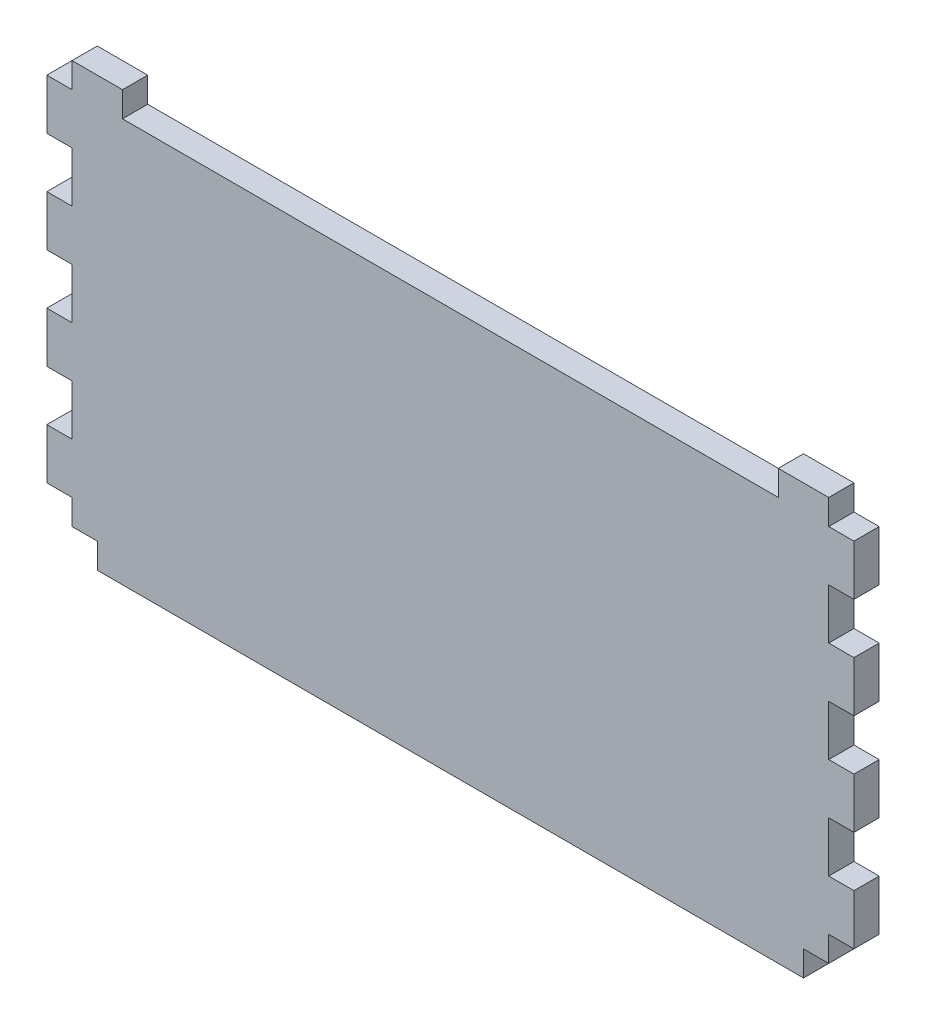
SolidWorks part; units mm, degrees
ref_plane "Plan de face" through (0, 0, 0) normal (0, 0, 1) x (1, 0, 0)
ref_plane "Plan de dessus" through (0, 0, 0) normal (0, 1, 0) x (1, 0, 0)
ref_plane "Plan de droite" through (0, 0, 0) normal (1, 0, 0) x (0, 0, -1)
sketch "Esquisse1" plane through (0, 0, 0) normal (0, 0, 1) x (1, 0, 0)
  line L32 (-83.2481, -165.0972) -> (-83.2481, -160.0972)
  line L33 (-83.2481, -85.0972) -> (66.7519, -85.0972)
  line L50 (-83.2481, -165.0972) -> (66.7519, -165.0972)
  line L52 (-83.2481, -90.0972) -> (-88.2481, -90.0972)
  line L54 (-83.2481, -100.0972) -> (-88.2481, -100.0972)
  line L55 (-88.2481, -90.0972) -> (-88.2481, -100.0972)
  line L56 (-83.2481, -110.0972) -> (-88.2481, -110.0972)
  line L58 (-83.2481, -120.0972) -> (-88.2481, -120.0972)
  line L59 (-88.2481, -110.0972) -> (-88.2481, -120.0972)
  line L60 (-83.2481, -130.0972) -> (-88.2481, -130.0972)
  line L62 (-83.2481, -140.0972) -> (-88.2481, -140.0972)
  line L63 (-88.2481, -130.0972) -> (-88.2481, -140.0972)
  line L64 (-83.2481, -150.0972) -> (-88.2481, -150.0972)
  line L66 (-83.2481, -160.0972) -> (-88.2481, -160.0972)
  line L67 (-88.2481, -150.0972) -> (-88.2481, -160.0972)
  line L68 (-83.2481, -150.0972) -> (-83.2481, -140.0972)
  line L69 (-83.2481, -130.0972) -> (-83.2481, -120.0972)
  line L70 (-83.2481, -110.0972) -> (-83.2481, -100.0972)
  line L71 (-83.2481, -90.0972) -> (-83.2481, -85.0972)
  line L72 (66.7519, -165.0972) -> (66.7519, -160.0972)
  line L73 (66.7519, -90.0972) -> (71.7519, -90.0972)
  line L75 (66.7519, -100.0972) -> (71.7519, -100.0972)
  line L76 (71.7519, -90.0972) -> (71.7519, -100.0972)
  line L77 (66.7519, -110.0972) -> (71.7519, -110.0972)
  line L79 (66.7519, -120.0972) -> (71.7519, -120.0972)
  line L80 (71.7519, -110.0972) -> (71.7519, -120.0972)
  line L81 (66.7519, -130.0972) -> (71.7519, -130.0972)
  line L83 (66.7519, -140.0972) -> (71.7519, -140.0972)
  line L84 (71.7519, -130.0972) -> (71.7519, -140.0972)
  line L85 (66.7519, -150.0972) -> (71.7519, -150.0972)
  line L87 (66.7519, -160.0972) -> (71.7519, -160.0972)
  line L88 (71.7519, -150.0972) -> (71.7519, -160.0972)
  line L89 (66.7519, -150.0972) -> (66.7519, -140.0972)
  line L90 (66.7519, -130.0972) -> (66.7519, -120.0972)
  line L91 (66.7519, -110.0972) -> (66.7519, -100.0972)
  line L92 (66.7519, -90.0972) -> (66.7519, -85.0972)
  dimension "D1" = 150
  dimension "D2" = 80
  dimension "D3" = 5
  dimension "D4" = 10
  dimension "D6" = 5
  dimension "D7" = 10
  dimension "D8" = 10
  dimension "D9" = 10
  dimension "D10" = 10
  dimension "D11" = 10
  dimension "D12" = 10
  dimension "D13" = 5
  dimension "D14" = 10
  dimension "D16" = 10
  dimension "D17" = 10
  dimension "D18" = 10
  dimension "D20" = 10
  dimension "D22" = 10
  dimension "D23" = 10
extrude "Boss.-Extru.1" add sketch "Esquisse1" along normal blind 5 contours L33 L92 L73 L76 L75 L91 L77 L80 L79 L90 L81 L84 L83 L89 L85 L88 L87 L72 L50 L32 L66 L67 L64 L68 L62 L63 L60 L69 L58 L59 L56 L70 L54 L55 L52 L71
sketch "Esquisse2" plane through (0, 0, 5) normal (0, 0, 1) x (1, 0, 0)
  line L0 (-83.2481, -85.0972) -> (66.7519, -85.0972) construction
  line L1 (-73.2481, -85.0972) -> (56.7519, -85.0972)
  line L2 (-73.2481, -85.0972) -> (-73.2481, -90.0972)
  line L3 (-73.2481, -90.0972) -> (56.7519, -90.0972)
  line L4 (56.7519, -85.0972) -> (56.7519, -90.0972)
  line L5 (-83.2481, -90.0972) -> (-83.2481, -85.0972) construction
  line L6 (66.7519, -90.0972) -> (66.7519, -85.0972) construction
  dimension "D1" = 5
  dimension "D2" = 10
  dimension "D3" = 10
extrude "Enlèv. mat.-Extru.1" cut sketch "Esquisse2" against normal blind 5
sketch "Esquisse3" plane through (0, 0, 5) normal (0, 0, 1) x (1, 0, 0)
  line L0 (-83.2481, -165.0972) -> (66.7519, -165.0972) construction
  line L1 (-78.2481, -165.0972) -> (61.7519, -165.0972)
  line L2 (-78.2481, -165.0972) -> (-78.2481, -170.0972)
  line L3 (-78.2481, -170.0972) -> (61.7519, -170.0972)
  line L4 (61.7519, -165.0972) -> (61.7519, -170.0972)
  line L5 (-83.2481, -165.0972) -> (-83.2481, -160.0972) construction
  dimension "D1" = 140
  dimension "D2" = 5
  dimension "D3" = 5
extrude "Boss.-Extru.2" add sketch "Esquisse3" against normal blind 5
